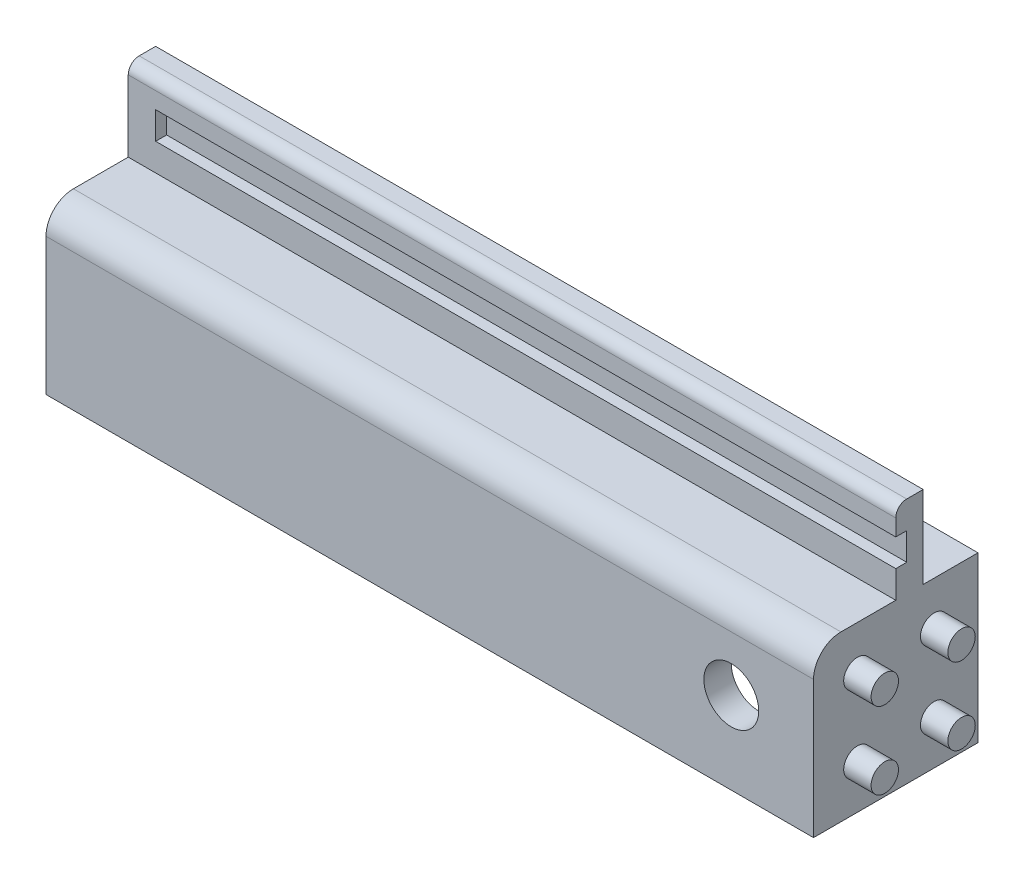
SolidWorks part; units mm, degrees
ref_plane "Front Plane" through (0, 0, 0) normal (0, 0, 1) x (1, 0, 0)
ref_plane "Top Plane" through (0, 0, 0) normal (0, 1, 0) x (1, 0, 0)
ref_plane "Right Plane" through (0, 0, 0) normal (1, 0, 0) x (0, 0, -1)
sketch "Sketch1" plane through (0, 0, 0) normal (0, 1, 0) x (1, 0, 0)
  line L0 (0, 0) -> (140, 0)
  line L1 (140, 0) -> (140, 30)
  line L2 (140, 30) -> (0, 30)
  line L3 (0, 30) -> (0, 0)
  dimension "D1" = 140
  dimension "D2" = 30
extrude "Boss-Extrude1" add sketch "Sketch1" along normal blind 30
shell "Shell1" thickness 5
sketch "Sketch3" plane through (0, 25, 0) normal (0, -1, 0) x (1, 0, 0)
  line L0 (50, -5) -> (50, -25)
  line L1 (5, -5) -> (135, -5) construction
  line L2 (135, -25) -> (5, -25) construction
  line L3 (50, -25) -> (55, -25)
  line L4 (55, -25) -> (55, -5)
  line L5 (55, -5) -> (50, -5)
  line L6 (5, -25) -> (5, -5) construction
  dimension "D1" = 5
  dimension "D2" = 45
extrude "Boss-Extrude2" add sketch "Sketch3" along normal blind 25
sketch "Sketch4" plane through (140, 0, 0) normal (1, 0, 0) x (0, 0, -1)
  line L0 (0, 30) -> (0, 0) construction
  line L1 (0, 30) -> (30, 30) construction
  line L2 (30, 30) -> (30, 0) construction
  line L3 (0, 0) -> (30, 0) construction
  circle A0 centre (8, 22) radius 2.5
  circle A1 centre (22, 22) radius 2.5
  circle A2 centre (8, 8) radius 2.5
  circle A3 centre (22, 8) radius 2.5
  dimension "D3" = 5
  dimension "D1" = 8
  dimension "D2" = 8
  dimension "D4" = 8
  dimension "D5" = 8
extrude "Boss-Extrude3" add sketch "Sketch4" along normal blind 5
sketch "Sketch5" plane through (0, 0, 0) normal (-1, 0, 0) x (0, 0, 1)
  line L0 (-30, 0) -> (0, 0) construction
  line L1 (-15, 30) -> (-15, 0) construction
  line L3 (-30, 30) -> (0, 30) construction
  circle A0 centre (-15, 15) radius 1.5
  point P3 (-15, 15)
  dimension "D1" = 3
extrude "Cut-Extrude1" cut sketch "Sketch5" against normal blind 20
sketch "Sketch9" plane through (0, 0, 0) normal (0, 0, 1) x (1, 0, 0)
  line L1 (140, 30) -> (140, 0) construction
  line L2 (125, 30) -> (125, 0) construction
  line L3 (0, 30) -> (140, 30) construction
  line L4 (0, 0) -> (140, 0) construction
  circle A1 centre (125, 15) radius 5
  point P11 (125, 15)
  dimension "D3" = 10
  dimension "D4" = 15
extrude "Cut-Extrude2" cut sketch "Sketch9" against normal through all both and the other way through all
sketch "Sketch10" plane through (0, 30, 0) normal (0, 1, 0) x (1, 0, 0)
  line L0 (140, 0) -> (140, 30) construction
  line L1 (0, 20) -> (140, 20)
  line L2 (0, 20) -> (0, 15)
  line L3 (0, 15) -> (140, 15)
  line L4 (140, 20) -> (140, 15)
  line L8 (140, 30) -> (0, 30) construction
  line L9 (0, 30) -> (0, 0) construction
  dimension "D1" = 10
extrude "Boss-Extrude5" add sketch "Sketch10" along normal blind 15
sketch "Sketch11" plane through (0, 0, -15) normal (0, 0, 1) x (1, 0, 0)
  line L0 (140, 45) -> (140, 30) construction
  line L1 (5, 40) -> (140, 40)
  line L2 (5, 40) -> (5, 35)
  line L3 (5, 35) -> (140, 35)
  line L4 (140, 40) -> (140, 35)
  line L5 (0, 45) -> (140, 45) construction
  line L6 (0, 45) -> (0, 30) construction
  dimension "D1" = 5
  dimension "D2" = 5
  dimension "D3" = 5
extrude "Cut-Extrude3" cut sketch "Sketch11" against normal blind 2
fillet "Fillet1" radius 2 1 edges at (70, 45, -15)
hole_wizard "CSK for M5 Flat Head Machine Screw1" positions "Sketch12" profile "Sketch13" countersink size "M5" standard "ANSI Metric"
sketch "Sketch12" plane through (0, 0, 0) normal (-1, 0, 0) x (0, 0, 1)
  point P0 (-15, 15)
sketch "Sketch13" plane through (0, 15, -15) normal (0, 1, 0) x (0, 0, 1)
  line L0 (0, 0) -> (0, 21.6524)
  line L1 (0, 21.6524) -> (2.75, 20)
  line L2 (2.75, 20) -> (2.75, 2.45)
  line L3 (2.75, 2.45) -> (5.2, 0)
  line L5 (5.2, 0) -> (0, 0)
  line L6 (-2.75, 2.45) -> (-5.2, 0) construction
  line L10 (0, 21.6524) -> (-2.75, 20) construction
  line L11 (0, -6.35) -> (0, 107.95) construction
  dimension "Hole Dia." = 5.5
  dimension "Hole Depth" = 20
  dimension "Near C'Sink Dia." = 10.4
  dimension "Near C'Sink Angle" = 90
  dimension "Drill Angle" = 118
fillet "Fillet2" radius 5 1 edges at (70, 30, 0)
